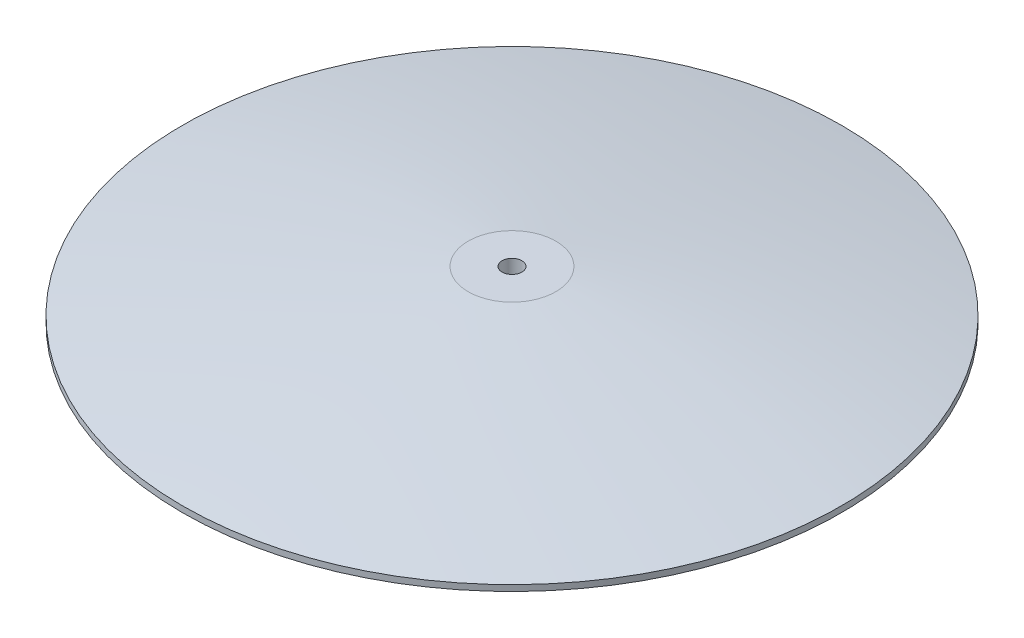
SolidWorks part; units mm, degrees
ref_plane "前视基准面" through (0, 0, 0) normal (0, 0, 1) x (1, 0, 0)
ref_plane "上视基准面" through (0, 0, 0) normal (0, 1, 0) x (1, 0, 0)
ref_plane "右视基准面" through (0, 0, 0) normal (1, 0, 0) x (0, 0, -1)
sketch "草图2" plane through (0, 0, 0) normal (0, 0, 1) x (1, 0, 0)
  line L0 (0, 0) -> (55, 0) construction
  line L1 (55, 0) -> (55, 1)
  line L2 (55, 1) -> (0, 8.7297) construction
  line L3 (0, 8.7297) -> (0, 0) construction
  line L4 (0, 8.7297) -> (0, 5.2297)
  line L5 (0, 8.1014) -> (7.3141, 8.1014)
  spline S0 degree 2 poles (55, 0) (27.6852, 4.6816) (0, 5.2297) knots 0 0 0 1 1 1
  spline S1 degree 2 poles (55, 1) (27.7359, 6.5755) (0, 8.7297) knots 0 0 0 1 1 1
  point P7 (7.3141, 8.1014)
  dimension "D1" = 55
  dimension "D2" = 1
  dimension "D3" = 8
  dimension "D4" = 3.5
revolve "旋转1" add sketch "草图2" angle 360 about L3
sketch "草图3" plane through (0, 8.1014, 0) normal (0, 1, 0) x (1, 0, 0)
  circle A0 centre (0, 0) radius 1.65
  dimension "D1" = 3.3
extrude "切除-拉伸1" cut sketch "草图3" against normal blind 10
